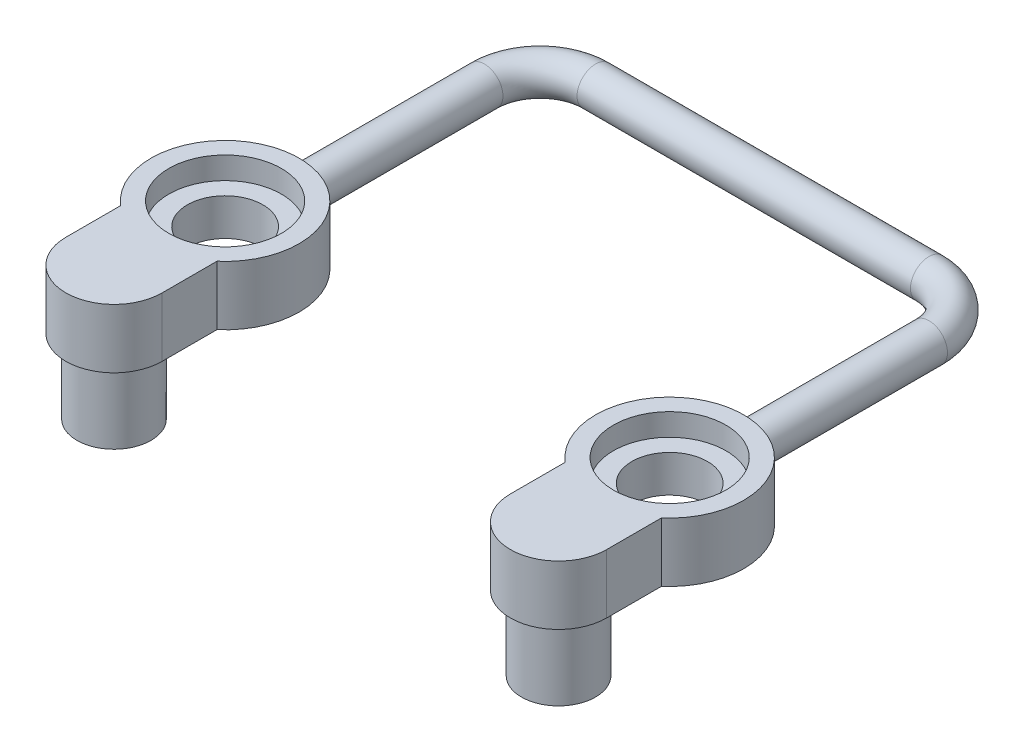
SolidWorks part; units mm, degrees
material "Cast Alloy Steel"
ref_plane "Front Plane" through (0, 0, 0) normal (0, 0, 1) x (1, 0, 0)
ref_plane "Top Plane" through (0, 0, 0) normal (0, 1, 0) x (1, 0, 0)
ref_plane "Right Plane" through (0, 0, 0) normal (1, 0, 0) x (0, 0, -1)
sketch "Sketch1" plane through (0, 0, 0) normal (0, 1, 0) x (1, 0, 0)
  line L0 (-46.355, -19.05) -> (-46.355, -9.6512)
  line L1 (-29.845, -19.05) -> (-29.845, -9.6512)
  line L2 (0, 0) -> (0, -19.05) construction
  line L3 (29.845, -19.05) -> (29.845, -9.6512)
  line L4 (46.355, -19.05) -> (46.355, -9.6512)
  arc A0 (-29.845, -9.6512) -> (-46.355, -9.6512) centre (-38.1, 0) ccw
  arc A1 (-46.355, -19.05) -> (-29.845, -19.05) centre (-38.1, -19.05) ccw
  circle A2 centre (-38.1, 0) radius 6.477
  circle A3 centre (38.1, 0) radius 6.477
  arc A4 (46.355, -19.05) -> (29.845, -19.05) centre (38.1, -19.05) cw
  arc A5 (29.845, -9.6512) -> (46.355, -9.6512) centre (38.1, 0) cw
  dimension "D1" = 25.4
  dimension "D3" = 16.51
  dimension "D5" = 12.954
  dimension "D2" = 38.1
  dimension "D4" = 19.05
extrude "Boss-Extrude1" add sketch "Sketch1" along normal mid plane 10.16
sketch "Sketch2" plane through (0, -5.08, 0) normal (0, -1, 0) x (1, 0, 0)
  circle A0 centre (-38.1, 19.05) radius 6.35
  circle A1 centre (38.1, 19.05) radius 6.35
  dimension "D1" = 12.7
extrude "Boss-Extrude2" add sketch "Sketch2" along normal blind 12.7
sketch "Sketch3" plane through (0, 5.08, 0) normal (0, 1, 0) x (1, 0, 0)
  circle A0 centre (-38.1, 0) radius 9.652
  circle A1 centre (38.1, 0) radius 9.652
  dimension "D1" = 19.304
extrude "Cut-Extrude1" cut sketch "Sketch3" against normal blind 3.81
ref_plane "Plane1" through (0, 0, -12.192) normal (0, 0, 1) x (1, 0, 0)
sketch "Sketch5" plane through (0, 0, -12.192) normal (0, 0, 1) x (1, 0, 0)
  line L0 (46.355, 5.08) -> (29.845, 5.08) construction
  circle A0 centre (38.1, 0) radius 3.175
  point P5 (38.1, 5.08)
  dimension "D1" = 38.1
  dimension "D3" = 6.35
  dimension "D2" = 5.08
sketch "Sketch6" plane through (0, 0, 0) normal (0, 1, 0) x (1, 0, 0)
  line L0 (38.1, 12.192) -> (38.1, 44.45)
  line L1 (34.925, 12.192) -> (41.275, 12.192) construction
  line L2 (-38.1, 44.45) -> (-38.1, 12.192)
  line L3 (-28.575, 53.975) -> (28.575, 53.975)
  arc A0 (-38.1, 44.45) -> (-28.575, 53.975) centre (-28.575, 44.45) cw
  arc A1 (38.1, 44.45) -> (28.575, 53.975) centre (28.575, 44.45) ccw
  dimension "D3" = 9.525
  dimension "D1" = 53.975
  dimension "D2" = 76.2
sweep "Sweep1" add profiles "Sketch5" path "Sketch6"
